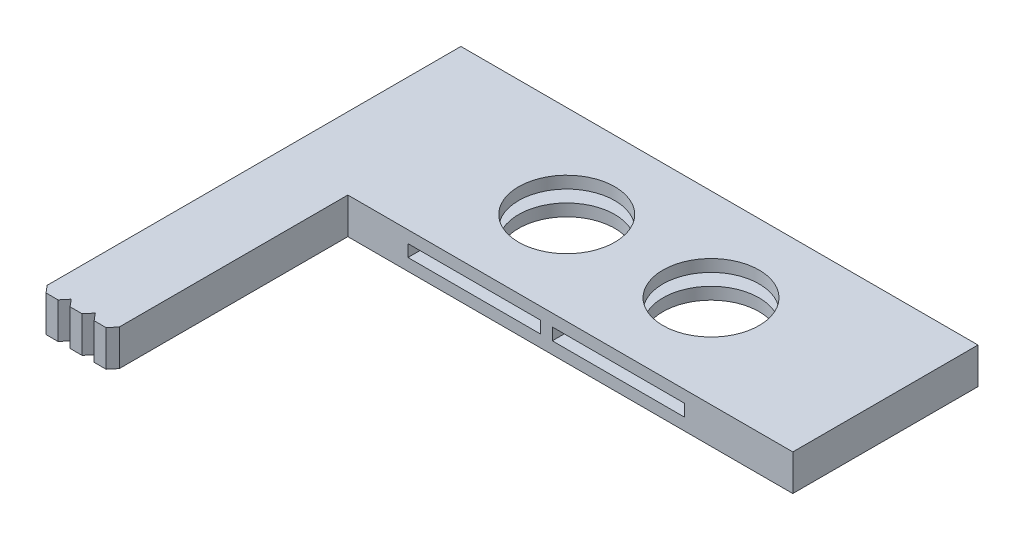
SolidWorks part; units mm, degrees
ref_plane "Front Plane" through (0, 0, 0) normal (0, 0, 1) x (1, 0, 0)
ref_plane "Top Plane" through (0, 0, 0) normal (0, 1, 0) x (1, 0, 0)
ref_plane "Right Plane" through (0, 0, 0) normal (1, 0, 0) x (0, 0, -1)
sketch "Sketch1" plane through (0, 0, 0) normal (0, 1, 0) x (1, 0, 0)
  line L0 (43, 7.7) -> (43, -7.7)
  line L1 (43, 7.7) -> (0, 7.7)
  line L2 (0, 7.7) -> (0, -26.7)
  line L5 (6, -7.7) -> (43, -7.7)
  line L6 (-47.7355, 0) -> (57.1135, 0) construction
  line L7 (0, -26.7) -> (0.5009, -27.3)
  line L8 (0.5009, -27.3) -> (1.4991, -27.3)
  line L9 (2, -26.7) -> (1.4991, -27.3)
  line L10 (1, -25.7079) -> (1, -27.6501) construction
  line L11 (2, -26.7) -> (2.5009, -27.3)
  line L12 (3, -25.7079) -> (3, -27.6501) construction
  line L13 (4, -26.7) -> (3.4991, -27.3)
  line L14 (4, -26.7) -> (4.5009, -27.3)
  line L15 (5, -25.7079) -> (5, -27.6501) construction
  line L16 (6, -26.7) -> (5.4991, -27.3)
  line L18 (7, -25.7079) -> (7, -27.6501) construction
  line L23 (2.5009, -27.3) -> (3.4991, -27.3)
  line L24 (4.5009, -27.3) -> (5.4991, -27.3)
  line L26 (8, -26.7) -> (7.4991, -27.3) [skipped]
  line L27 (6, -26.7) -> (6.5009, -27.3) [skipped]
  line L28 (6, -26.7) -> (6, -7.7)
  circle A0 centre (16.5, 0) radius 4
  circle A1 centre (28.5, 0) radius 4
  dimension "D5" = 8
  dimension "D1" = 15.4
  dimension "D2" = 10.5
  dimension "D3" = 43
  dimension "D4" = 35
  dimension "D6" = 12
  dimension "D7" = 0.6
  dimension "D9" = 2
  dimension "D10" = 4
extrude "Boss-Extrude1" add sketch "Sketch1" along normal blind 3
sketch "Sketch2" plane through (0, 0, 7.7) normal (0, 0, 1) x (1, 0, 0)
  line L0 (8, 1.5) -> (43, 1.5) construction
  line L1 (11, 2) -> (22, 2)
  line L2 (11, 2) -> (11, 1)
  line L3 (11, 1) -> (22, 1)
  line L4 (22, 2) -> (22, 1)
  line L5 (23, 2) -> (34, 2)
  line L6 (23, 2) -> (23, 1)
  line L7 (23, 1) -> (34, 1)
  line L8 (34, 2) -> (34, 1)
  line L13 (16.5, 3.4489) -> (16.5, -1.3527) construction
  line L14 (43, 3) -> (43, 0) construction
  line L15 (12.5, 3) -> (12.5, 0) construction
  line L16 (20.5, 0) -> (20.5, 3) construction
  line L17 (28.5, 3.4489) -> (28.5, -1.3527) construction
  line L18 (24.5, 3) -> (24.5, 0) construction
  line L19 (32.5, 0) -> (32.5, 3) construction
  dimension "D1" = 11
  dimension "D2" = 11
  dimension "D3" = 1
extrude "Cut-Extrude1" cut sketch "Sketch2" against normal offset from surface (13.4 mm away) 2 up to face at (21.5, 1.5, -7.7)
